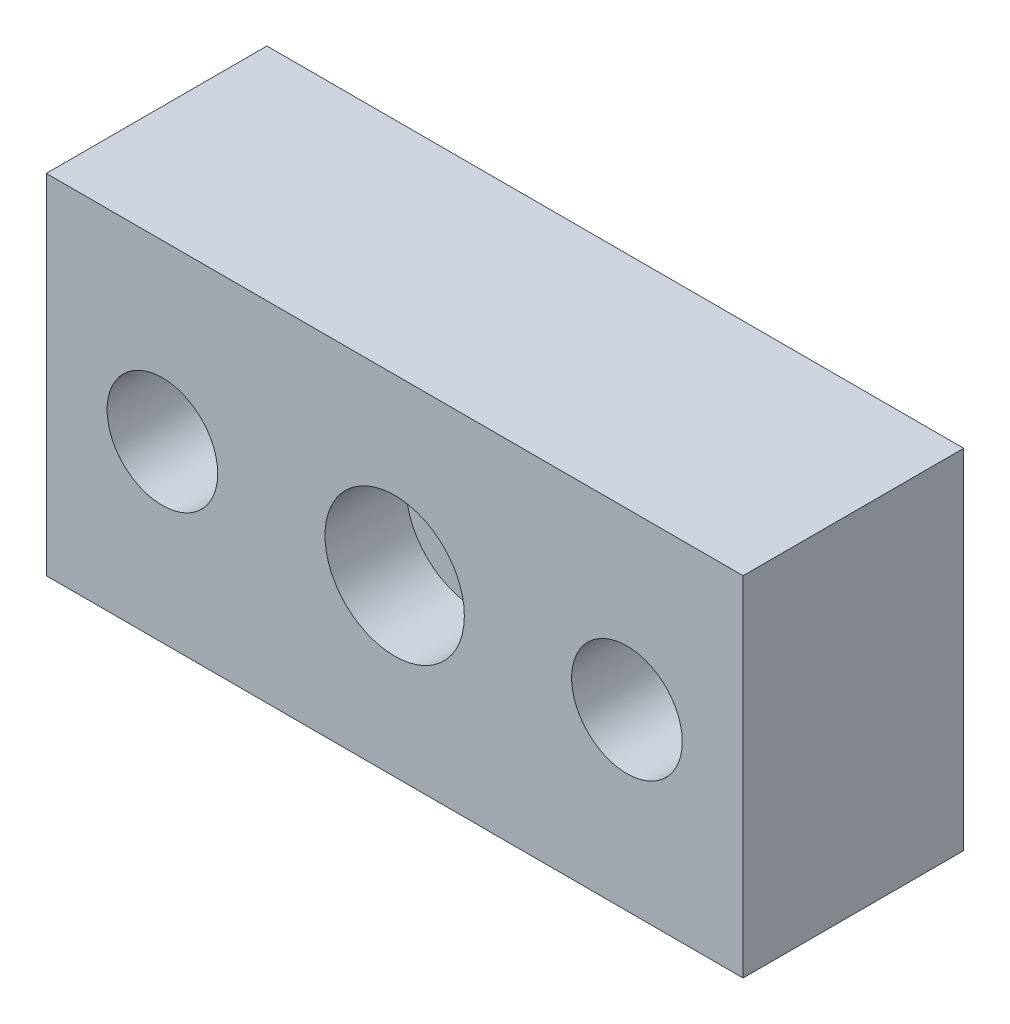
SolidWorks part; units mm, degrees
ref_plane "Front" through (0, 0, 0) normal (0, 0, 1) x (1, 0, 0)
ref_plane "Top" through (0, 0, 0) normal (0, 1, 0) x (1, 0, 0)
ref_plane "Right" through (0, 0, 0) normal (1, 0, 0) x (0, 0, -1)
sketch "Sketch1" plane through (0, 0, 0) normal (0, 0, 1) x (1, 0, 0)
  line L0 (-15, 0) -> (-10, 0) construction
  line L1 (-15, -7.5) -> (15, -7.5)
  line L2 (-15, -7.5) -> (-15, 7.5)
  line L3 (-15, 7.5) -> (15, 7.5)
  line L4 (15, -7.5) -> (15, 7.5)
  line L5 (-15, -7.5) -> (15, 7.5) construction
  line L6 (-15, 7.5) -> (15, -7.5) construction
  line L7 (-10, 0) -> (0, 0) construction
  line L8 (0, 0) -> (10, 0) construction
  line L9 (10, 0) -> (15, 0) construction
  circle A0 centre (0, 0) radius 1
  circle A1 centre (10, 0) radius 2.3813
  circle A2 centre (-10, 0) radius 2.3813
  point P0 (0, 0)
  dimension "D4" = 2
  dimension "D5" = 4.7625
  dimension "D1" = 30
  dimension "D2" = 15
  dimension "D3" = 20
extrude "Boss-Extrude1" add sketch "Sketch1" along normal blind 9.5
sketch "Sketch2" plane through (0, 0, 9.5) normal (0, 0, 1) x (1, 0, 0)
  circle A0 centre (0, 0) radius 3
  dimension "D1" = 6
extrude "Cut-Extrude1" cut sketch "Sketch2" against normal blind 3.5
sketch "Sketch3" plane through (0, 0, 0) normal (0, 0, -1) x (-1, 0, 0)
  circle A0 centre (0, 0) radius 3
  dimension "D1" = 6
extrude "Cut-Extrude2" cut sketch "Sketch3" against normal blind 3
